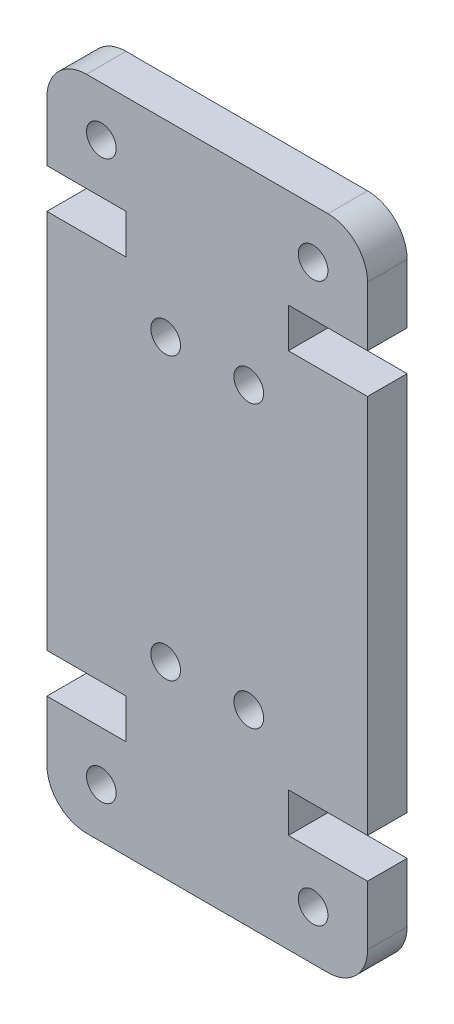
SolidWorks part; units mm, degrees
ref_plane "Front Plane" through (0, 0, 0) normal (0, 0, 1) x (1, 0, 0)
ref_plane "Top Plane" through (0, 0, 0) normal (0, 1, 0) x (1, 0, 0)
ref_plane "Right Plane" through (0, 0, 0) normal (1, 0, 0) x (0, 0, -1)
sketch "Sketch1" plane through (0, 0, 0) normal (0, 0, 1) x (1, 0, 0)
  line L0 (0, 26.21) -> (0, 7)
  line L1 (16.2, 2) -> (16.2, 5)
  line L2 (12.2, 5) -> (16.2, 5)
  line L3 (2, 0) -> (14.2, 0)
  line L4 (16.2, 7) -> (12.2, 7)
  line L5 (12.2, 7) -> (12.2, 5)
  line L6 (16.2, 26.21) -> (16.2, 7)
  line L7 (4, 7) -> (4, 5)
  line L8 (0, 31.21) -> (0, 28.21)
  line L9 (4, 28.21) -> (0, 28.21)
  line L10 (0, 7) -> (4, 7)
  line L11 (0, 26.21) -> (4, 26.21)
  line L12 (4, 5) -> (0, 5)
  line L13 (4, 26.21) -> (4, 28.21)
  line L14 (12.2, 26.21) -> (12.2, 28.21)
  line L15 (16.2, 26.21) -> (12.2, 26.21)
  line L16 (0, 2) -> (0, 5)
  line L17 (2, 33.21) -> (14.2, 33.21)
  line L18 (12.2, 28.21) -> (16.2, 28.21)
  line L19 (16.2, 31.21) -> (16.2, 28.21)
  line L20 (0, 16.605) -> (16.2, 16.605) construction
  line L21 (8.1, 33.21) -> (8.1, 0) construction
  circle A0 centre (13.45, 2.5) radius 0.75
  circle A1 centre (10.2, 9.5) radius 0.75
  arc A2 (16.2, 2) -> (14.2, 0) centre (14.2, 2) cw
  circle A3 centre (2.75, 30.71) radius 0.75
  circle A4 centre (6, 23.71) radius 0.75
  arc A5 (0, 2) -> (2, 0) centre (2, 2) ccw
  arc A6 (0, 31.21) -> (2, 33.21) centre (2, 31.21) cw
  circle A7 centre (6, 9.5) radius 0.75
  arc A8 (16.2, 31.21) -> (14.2, 33.21) centre (14.2, 31.21) ccw
  circle A9 centre (2.75, 2.5) radius 0.75
  circle A10 centre (10.2, 23.71) radius 0.75
  circle A11 centre (13.45, 30.71) radius 0.75
  point P15 (8.1, 16.605)
  dimension "D1" = 1.5
  dimension "D2" = 2
  dimension "D3" = 2.75
  dimension "D4" = 6
  dimension "D5" = 8.1
  dimension "D6" = 2.5
  dimension "D7" = 5
  dimension "D9" = 9.5
  dimension "D10" = 16.605
extrude "Boss-Extrude1" add sketch "Sketch1" along normal blind 4
sketch "Sketch2" plane through (0, 0, 0) normal (0, 0, 1) x (1, 0, 0)
  line L0 (0, 0) -> (16.2, 0)
  line L1 (16.2, 0) -> (16.2, 33.21)
  line L2 (16.2, 33.21) -> (0, 33.21)
  line L3 (0, 33.21) -> (0, 0)
extrude "Cut-Extrude2" cut sketch "Sketch2" along normal blind 2
equation "\"D5@Sketch1\"= \"fingerWidth@parametersSketch@prostheticParameters.SLDPRT\" / 2'PIP width"
equation "\"D10@Sketch1\"= ( \"HL@parametersSketch@prostheticParameters.SLDPRT\" * 0.266 - 12 - 4 ) / 2 'PIP length - Sil. sht PIP-Sil Sht MIP"
